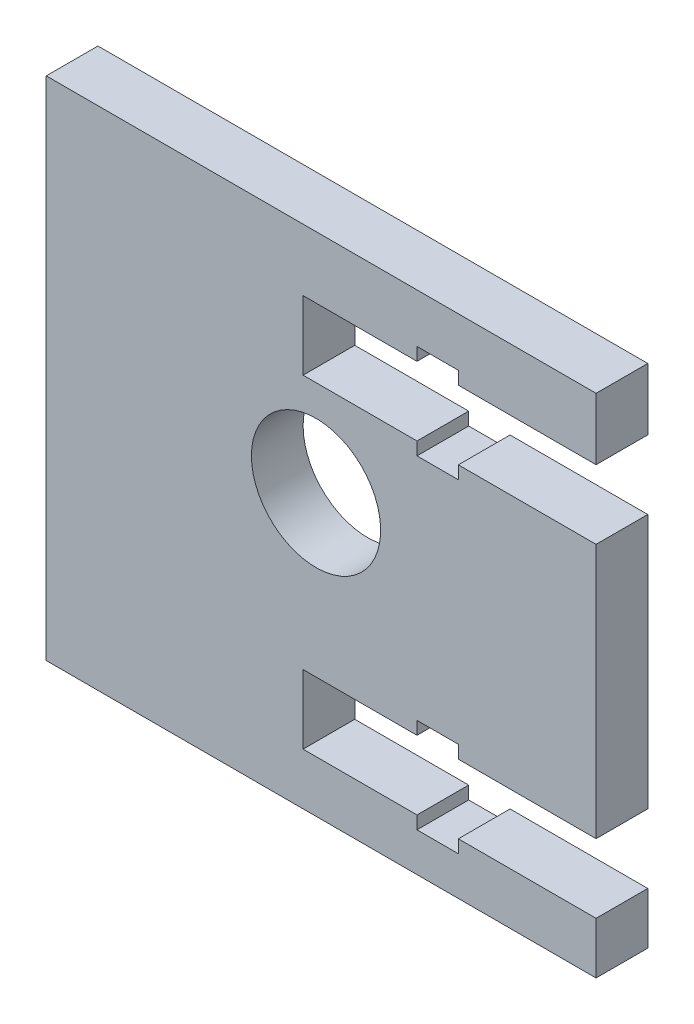
SolidWorks part; units mm, degrees
ref_plane "Front Plane" through (0, 0, 0) normal (0, 0, 1) x (1, 0, 0)
ref_plane "Top Plane" through (0, 0, 0) normal (0, 1, 0) x (1, 0, 0)
ref_plane "Right Plane" through (0, 0, 0) normal (1, 0, 0) x (0, 0, -1)
sketch "Sketch1" plane through (0, 0, 0) normal (0, 0, 1) x (1, 0, 0)
  line L1 (-2.3561, 83.56) -> (29.5456, 83.56)
  line L2 (-2.3561, 83.56) -> (-2.3561, 54.769)
  line L3 (-2.3561, 54.769) -> (29.5456, 54.769)
  line L4 (29.5456, 83.56) -> (29.5456, 54.769)
  dimension "D1" = 31.9018
  dimension "D2" = 28.791
  dimension "D3" = 83.56
  dimension "D4" = 2.3561
extrude "Boss-Extrude2" add sketch "Sketch1" along normal blind 3 contours L4 L3 L2 L1
sketch "Sketch3" plane through (0, 0, 0) normal (0, 0, -1) x (-1, 0, 0)
  line L0 (2.3561, 54.769) -> (-29.5456, 54.769) construction
  line L1 (2.3561, 83.56) -> (2.3561, 54.769) construction
  circle A1 centre (-13.2979, 71.0168) radius 3.75
  dimension "D1" = 7.5
  dimension "D2" = 16.2477
  dimension "D3" = 15.654
extrude "Cut-Extrude1" cut sketch "Sketch3" against normal blind 33
sketch "Sketch5" plane through (0, 0, 3) normal (0, 0, 1) x (1, 0, 0)
  line L1 (29.5456, 83.56) -> (29.5456, 54.769) construction
  line L5 (29.5456, 76.56) -> (21.5557, 76.56)
  line L6 (12.5456, 76.56) -> (12.5456, 80.56)
  line L7 (12.5456, 80.56) -> (19.1557, 80.56)
  line L8 (-2.3561, 83.56) -> (29.5456, 83.56) construction
  line L9 (19.1557, 80.56) -> (19.1557, 81.31)
  line L10 (19.1557, 81.31) -> (21.5557, 81.31)
  line L11 (21.5557, 81.31) -> (21.5557, 80.56)
  line L12 (19.1557, 76.56) -> (19.1557, 75.81)
  line L13 (19.1557, 75.81) -> (21.5557, 75.81)
  line L14 (21.5557, 75.81) -> (21.5557, 76.56)
  line L15 (29.5456, 69.1645) -> (-5.6198, 69.1645) construction
  line L16 (21.5557, 80.56) -> (29.5456, 80.56)
  line L17 (19.1557, 76.56) -> (12.5456, 76.56)
  line L18 (29.5456, 80.56) -> (29.5456, 76.56)
  line L19 (29.5456, 57.769) -> (29.5456, 61.769)
  line L20 (19.1557, 61.769) -> (12.5456, 61.769)
  line L21 (21.5557, 57.769) -> (29.5456, 57.769)
  line L22 (21.5557, 62.519) -> (21.5557, 61.769)
  line L23 (19.1557, 62.519) -> (21.5557, 62.519)
  line L24 (19.1557, 61.769) -> (19.1557, 62.519)
  line L25 (21.5557, 57.019) -> (21.5557, 57.769)
  line L26 (19.1557, 57.019) -> (21.5557, 57.019)
  line L27 (19.1557, 57.769) -> (19.1557, 57.019)
  line L28 (12.5456, 57.769) -> (19.1557, 57.769)
  line L29 (12.5456, 61.769) -> (12.5456, 57.769)
  line L30 (29.5456, 61.769) -> (21.5557, 61.769)
  dimension "D1" = 3
  dimension "D2" = 4
  dimension "D3" = 17
  dimension "D4" = 0.75
  dimension "D5" = 0.75
  dimension "D6" = 2.4
extrude "Cut-Extrude2" cut sketch "Sketch5" against normal blind 33 contours L18 L5 L14 L13 L12 L17 L6 L7 L9 L10 L11 L16 | L19 L30 L22 L23 L24 L20 L29 L28 L27 L26 L25 L21
sketch "Sketch6" plane through (0, 0, 3) normal (0, 0, 1) x (1, 0, 0)
  line L0 (-2.3561, 83.56) -> (29.5456, 83.56)
  line L1 (29.5456, 83.56) -> (29.5456, 84.15)
  line L2 (29.5456, 84.15) -> (-2.3561, 84.15)
  line L3 (-2.3561, 84.15) -> (-2.3561, 83.56)
  dimension "D1" = 0.59
extrude "Boss-Extrude3" add sketch "Sketch6" against normal blind 3
